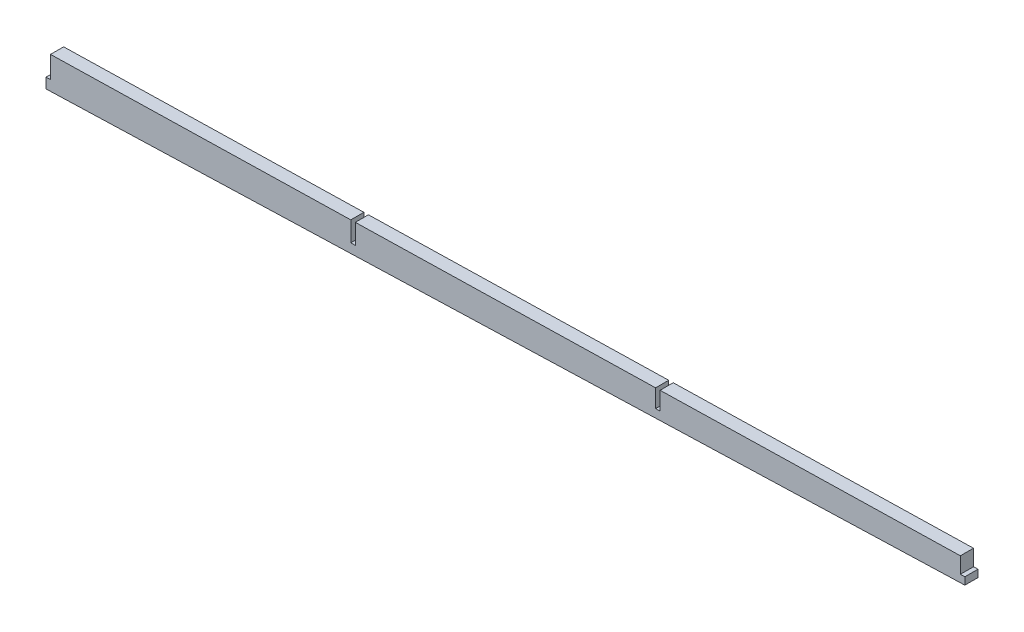
SolidWorks part; units mm, degrees
ref_plane "Спереди" through (0, 0, 0) normal (0, 0, 1) x (1, 0, 0)
ref_plane "Сверху" through (0, 0, 0) normal (0, 1, 0) x (1, 0, 0)
ref_plane "Справа" through (0, 0, 0) normal (1, 0, 0) x (0, 0, -1)
other "Configuration Table"
sketch "Эскиз1" plane through (0, 0, 0) normal (0, 1, 0) x (1, 0, 0)
  line L1 (-1000, 0) -> (-1000, 240)
  line L11 (-388, 184.92) -> (-391, 185.19)
  line L12 (-1000, 0) -> (-997, 0)
  line L14 (-797, 0) -> (-794, 0)
  line L16 (-594, 0) -> (-591, 0)
  line L18 (-997, 0) -> (-997, 240)
  line L19 (-391, 0) -> (-388, 0)
  line L20 (-797, 0) -> (-797, 261.7614)
  line L21 (-794, 0) -> (-794, 261.7614)
  line L22 (-797, 261.7614) -> (-794, 261.7614)
  line L23 (-388, 0) -> (-388, 184.92)
  line L24 (-391, 0) -> (-391, 185.19)
  line L25 (-1000, 240) -> (-997, 240)
  line L26 (-594, 0) -> (-594, 230.0818)
  line L27 (-594, 230.0818) -> (-591, 230.0818)
  line L28 (-591, 230.0818) -> (-591, 0)
ref_plane "Плоскость1" through (-1000, 0, 0) normal (1, 0, 0) x (0, 0, -1)
sketch "Эскиз4" plane through (-1000, 0, 0) normal (1, 0, 0) x (0, 0, -1)
  line L0 (70.5, 15) -> (70.5, -7)
  line L4 (70.5, -7) -> (79.5, -7)
  line L5 (79.5, -7) -> (79.5, 15)
  line L6 (79.5, 15) -> (70.5, 15)
ref_plane "Плоскость2" through (-388, 0, 0) normal (1, 0, 0) x (0, 0, -1)
sketch "Эскиз5" plane through (-388, 0, 0) normal (1, 0, 0) x (0, 0, -1)
  line L2 (61.14, 11) -> (52.14, 11)
  line L3 (52.14, 11) -> (52.14, -5)
  line L4 (52.14, -5) -> (61.14, -5)
  line L5 (61.14, 11) -> (61.14, -5)
loft "По сечениям1" add profiles "Эскиз4", "Эскиз5"
extrude "Вырез-Вытянуть2" cut sketch "Эскиз1" against normal blind 20
sketch "Эскиз6" plane through (0, 0, 0) normal (0, 1, 0) x (1, 0, 0)
  line L0 (-1095.206, 0) -> (-296.0695, 0) construction
  line L1 (-1000, 70.5) -> (-388, 52.14)
  line L2 (-388, 52.14) -> (-388, 61.14)
  line L3 (-388, 61.14) -> (-1000, 79.5)
  line L4 (-1000, 79.5) -> (-1000, 70.5)
  line L5 (-997, 70.41) -> (-997, 79.41)
  line L6 (-797, 64.41) -> (-797, 73.41)
  line L7 (-794, 64.32) -> (-794, 73.32)
  line L8 (-391, 52.23) -> (-391, 61.23)
  line L9 (-391, -52.23) -> (-391, -61.23)
  line L10 (-794, -64.32) -> (-794, -73.32)
  line L11 (-797, -64.41) -> (-797, -73.41)
  line L12 (-997, -70.41) -> (-997, -79.41)
  line L13 (-1000, -79.5) -> (-1000, -70.5)
  line L14 (-388, -61.14) -> (-391, -61.23)
  line L15 (-388, -52.14) -> (-388, -61.14)
  line L16 (-1000, -70.5) -> (-997, -70.41)
  line L17 (-797, -64.41) -> (-794, -64.32)
  line L18 (-997, -79.41) -> (-1000, -79.5)
  line L19 (-594, 58.32) -> (-594, 67.32)
  line L20 (-591, 58.23) -> (-591, 67.23)
  line L21 (-594, -58.32) -> (-594, -67.32)
  line L22 (-591, -58.23) -> (-591, -67.23)
  line L23 (-391, -52.23) -> (-388, -52.14)
  line L24 (-591, -67.23) -> (-594, -67.32)
  line L25 (-794, -73.32) -> (-797, -73.41)
  line L26 (-594, -58.32) -> (-591, -58.23)
sketch "Эскиз7" plane through (-388, 0, 0) normal (1, 0, 0) x (0, 0, -1)
  line L1 (-61.14, -5) -> (-52.14, -5)
  line L8 (-52.14, -5) -> (-52.14, 11)
  line L9 (-61.14, 11) -> (-52.14, 11)
  line L10 (-61.14, -5) -> (-61.14, 11)
sketch "Эскиз8" plane through (-1000, 0, 0) normal (-1, 0, 0) x (0, 0, 1)
  line L8 (70.5, -7) -> (79.5, -7)
  line L10 (79.5, -7) -> (79.5, 15)
  line L11 (70.5, 15) -> (70.5, -7)
  line L12 (79.5, 15) -> (70.5, 15)
loft "По сечениям4" add profiles "Эскиз7", "Эскиз8"
extrude "Вырез-Вытянуть7" cut sketch "Эскиз6" along normal blind 30 contours L12 L18 L13 L16 | L10 L25 L11 L17 | L22 L24 L21 L26 | L15 L14 L9 L23
sketch "Эскиз10" plane through (0, 0, 0) normal (0, 1, 0) x (1, 0, 0)
  line L1 (-1040.9949, 141.4623) -> (-325.4369, 141.4623)
  line L2 (-1040.9949, 141.4623) -> (-1040.9949, -6.3436)
  line L3 (-1040.9949, -6.3436) -> (-325.4369, -6.3436)
  line L4 (-325.4369, 141.4623) -> (-325.4369, -6.3436)
extrude "Вырез-Вытянуть8" cut sketch "Эскиз10" against normal through all both and the other way through all
